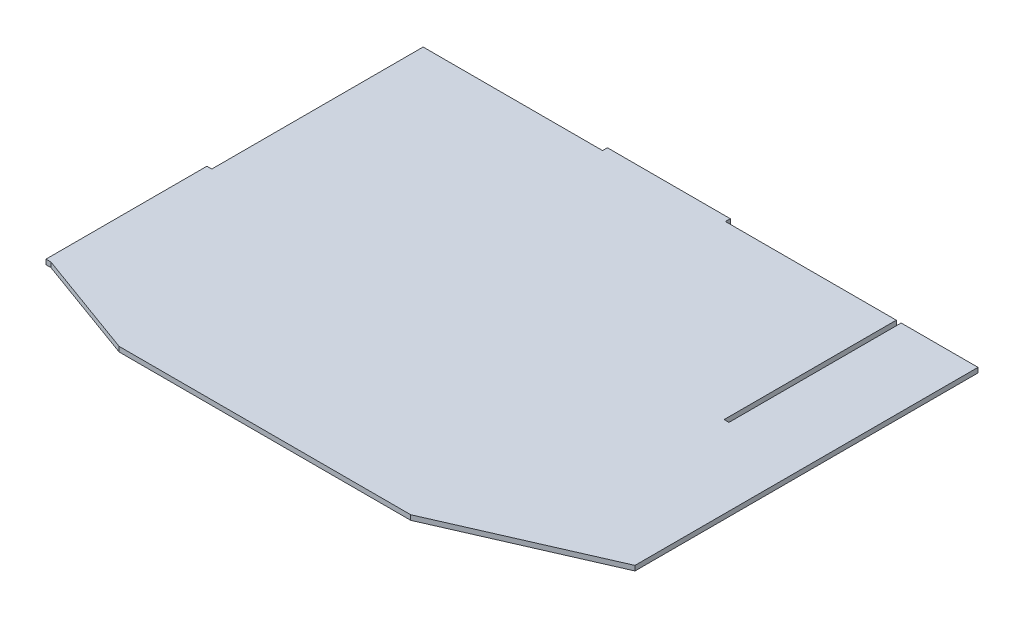
SolidWorks part; units mm, degrees
material "6061-T6 (SS)"
ref_plane "X-Y Datum" through (0, 0, 0) normal (0, 0, 1) x (1, 0, 0)
ref_plane "X-Z Datum" through (0, 0, 0) normal (0, 1, 0) x (1, 0, 0)
ref_plane "Y-Z Datum" through (0, 0, 0) normal (1, 0, 0) x (0, 0, -1)
sketch "Sketch1" plane through (0, 0, 0) normal (0, 0, 1) x (1, 0, 0)
  line L1 (-154.0556, -1.5875) -> (154.0556, -1.5875)
  line L2 (-154.0556, -1.5875) -> (-154.0556, 1.5875)
  line L3 (-154.0556, 1.5875) -> (154.0556, 1.5875)
  line L4 (154.0556, -1.5875) -> (154.0556, 1.5875)
  line L5 (-154.0556, -1.5875) -> (154.0556, 1.5875) construction
  line L6 (-154.0556, 1.5875) -> (154.0556, -1.5875) construction
  point P0 (0, 0)
  dimension "D1" = 3.175
  dimension "D2" = 308.1112
extrude "Boss-Extrude1" add sketch "Sketch1" along normal blind 267.83
sketch "Sketch3" plane through (154.0556, 0, 0) normal (1, 0, 0) x (0, 0, -1)
  line L0 (-267.83, 1.5875) -> (0, 1.5875) construction
  line L1 (-267.83, -1.5875) -> (-112.128, -1.5875)
  line L2 (-267.83, -1.5875) -> (-267.83, 1.5875)
  line L3 (-267.83, 1.5875) -> (-112.128, 1.5875)
  line L4 (-112.128, -1.5875) -> (-112.128, 1.5875)
  dimension "D1" = 155.702
extrude "Boss-Extrude3" add sketch "Sketch3" along normal blind 3.175
sketch "Sketch4" plane through (0, 0, 267.83) normal (0, 0, 1) x (1, 0, 0)
  line L1 (157.2306, -1.5875) -> (207.2686, -1.5875)
  line L2 (157.2306, -1.5875) -> (157.2306, 1.5875)
  line L3 (157.2306, 1.5875) -> (207.2686, 1.5875)
  line L4 (207.2686, -1.5875) -> (207.2686, 1.5875)
  dimension "D1" = 3.175
  dimension "D2" = 50.038
extrude "Boss-Extrude4" add sketch "Sketch4" against normal blind 267.83
sketch "Sketch6" plane through (0, 1.5875, 0) normal (0, 1, 0) x (1, 0, 0)
  line L0 (105.6686, -267.83) -> (105.6686, -223.38)
  line L1 (207.2686, -267.83) -> (-154.0556, -267.83) construction
  line L2 (207.2686, -223.38) -> (105.6686, -223.38)
  line L3 (207.2686, 0) -> (207.2686, -267.83) construction
  line L4 (105.6686, -267.83) -> (207.2686, -223.38)
  line M9 (-154.0556, -267.83) -> (207.2686, -267.83)
  line M10 (207.2686, -267.83) -> (207.2686, 0)
  dimension "D1" = 44.45
  dimension "D2" = 101.6
extrude "Cut-Extrude1" cut sketch "Sketch6" against normal through all contours L4 M9 M10
sketch "Sketch8" plane through (0, 0, 0) normal (0, 0, -1) x (-1, 0, 0)
  line L1 (37.216, 1.5875) -> (-42.784, 1.5875)
  line L2 (37.216, 1.5875) -> (37.216, -1.5875)
  line L3 (37.216, -1.5875) -> (-42.784, -1.5875)
  line L4 (-42.784, 1.5875) -> (-42.784, -1.5875)
extrude "Boss-Extrude6" add sketch "Sketch8" along normal blind 3.175
sketch "Sketch11" plane through (0, -1.5875, 0) normal (0, -1, 0) x (1, 0, 0)
  line L0 (-84.2056, 267.83) -> (-84.2056, 242.43)
  line L1 (-154.0556, 267.83) -> (105.6686, 267.83) construction
  line L2 (-154.0556, 242.43) -> (-84.2056, 242.43)
  line L3 (-154.0556, 267.83) -> (-154.0556, 0) construction
  line L4 (-154.0556, 242.43) -> (-84.2056, 267.83)
  line M4 (-154.0556, 267.83) -> (-154.0556, 0)
  line M18 (105.6686, 267.83) -> (-154.0556, 267.83)
  dimension "D1" = 69.85
  dimension "D2" = 25.4
extrude "Cut-Extrude3" cut sketch "Sketch11" against normal through all contours L4 M4 M18
sketch "Sketch13" plane through (-154.0556, 0, 0) normal (-1, 0, 0) x (0, 0, 1)
  line L1 (137.65, -1.598) -> (242.43, -1.598)
  line L2 (137.65, -1.598) -> (137.65, 1.5875)
  line L3 (137.65, 1.5875) -> (242.43, 1.5875)
  line L4 (242.43, -1.598) -> (242.43, 1.5875)
extrude "Boss-Extrude7" add sketch "Sketch13" along normal blind 3.175
